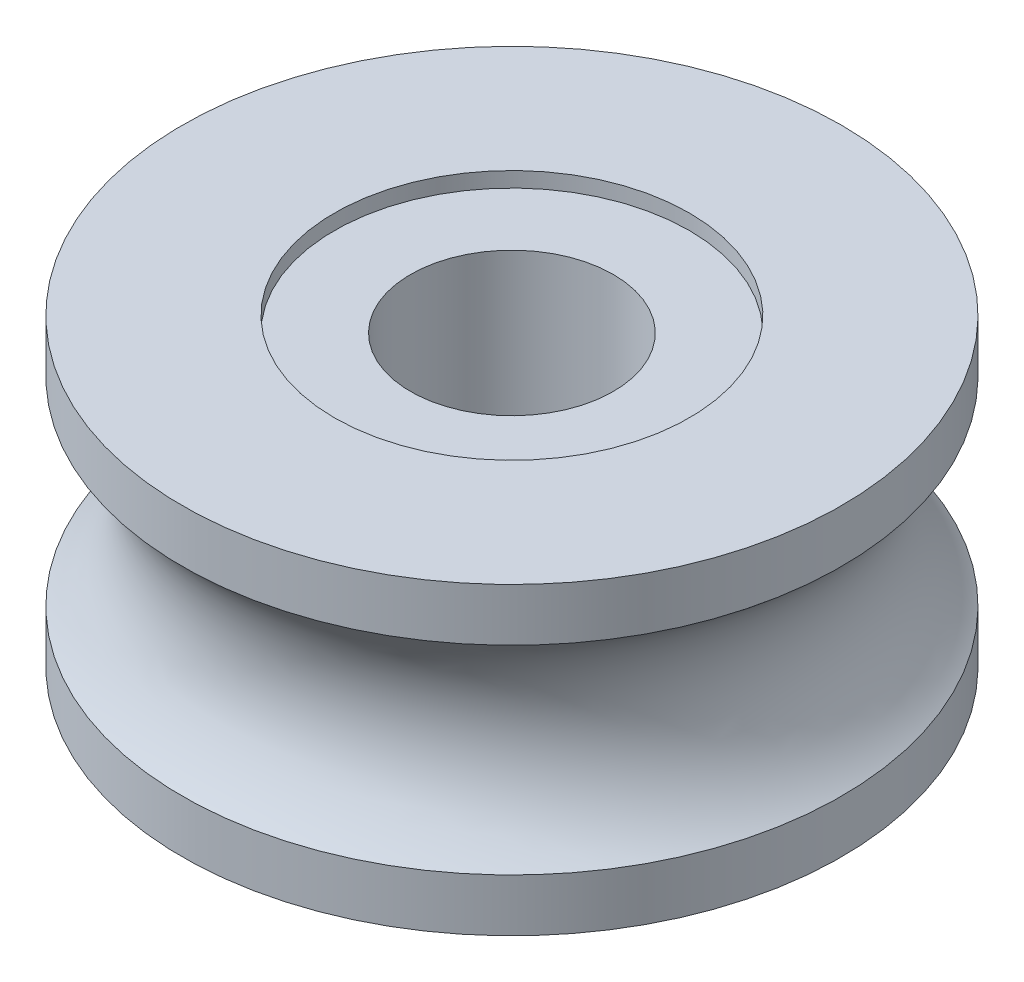
SolidWorks part; units mm, degrees
ref_plane "Спереди" through (0, 0, 0) normal (0, 0, 1) x (1, 0, 0)
ref_plane "Сверху" through (0, 0, 0) normal (0, 1, 0) x (1, 0, 0)
ref_plane "Справа" through (0, 0, 0) normal (1, 0, 0) x (0, 0, -1)
sketch "Эскиз1" plane through (0, 0, 0) normal (0, 0, 1) x (1, 0, 0)
  line L0 (2, -3.85) -> (2, 3.85)
  line L3 (6.5, -1.85) -> (3, -1.85)
  line L4 (3, -1.85) -> (3, -3.85)
  line L5 (3, -3.85) -> (2, -3.85)
  line L6 (0, 0) -> (0, 5.6) construction
  line L7 (6.5, -1.85) -> (6.5, -0.8115)
  line L8 (6.5, 4.15) -> (6.5, 3.1115)
  line L9 (6.5, 4.15) -> (3.5, 4.15)
  line L10 (3.5, 4.15) -> (3.5, 3.85)
  line L11 (3.5, 3.85) -> (2, 3.85)
  arc A0 (6.5, 3.1115) -> (6.5, -0.8115) centre (8.05, 1.15) ccw
  point P2 (2, 0)
  dimension "D2" = 2.5
  dimension "D1" = 2
  dimension "D3" = 3
  dimension "D4" = 6
  dimension "D5" = 8.05
  dimension "D6" = 8
  dimension "D7" = 6.5
  dimension "D8" = 0.3
  dimension "D9" = 3.5
revolve "Повернуть1" add sketch "Эскиз1" angle 360 about L6
ref_plane "Плоскость1" through (0, 1.15, 0) normal (0, 1, 0) x (1, 0, 0)
